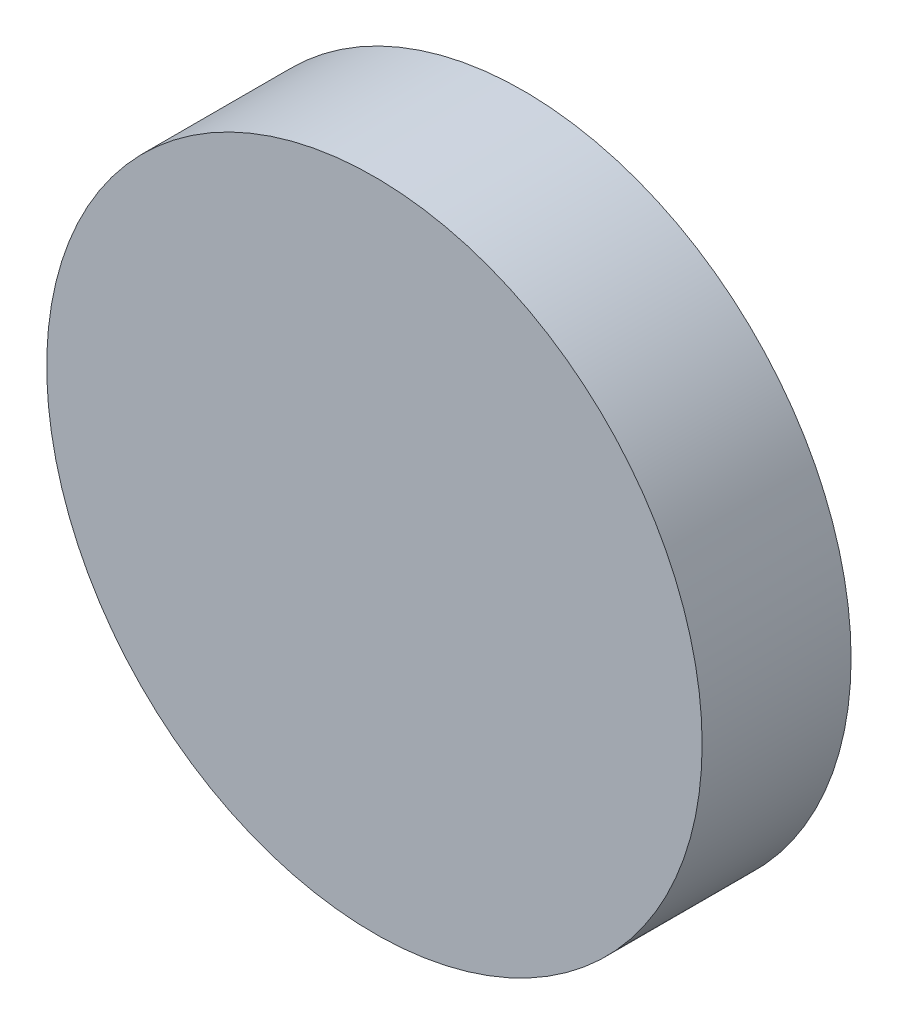
SolidWorks part; units mm, degrees
ref_plane "前视基准面" through (0, 0, 0) normal (0, 0, 1) x (1, 0, 0)
ref_plane "上视基准面" through (0, 0, 0) normal (0, 1, 0) x (1, 0, 0)
ref_plane "右视基准面" through (0, 0, 0) normal (1, 0, 0) x (0, 0, -1)
other "Configuration Table"
sketch "草图1" plane through (0, 0, 0) normal (0, 0, 1) x (1, 0, 0)
  circle A0 centre (0, 0) radius 55
extrude "凸台-拉伸1" add sketch "草图1" against normal blind 25
sketch "草图2" plane through (0, 0, 0) normal (0, 0, 1) x (1, 0, 0)
  circle A0 centre (0, 0) radius 12
sketch "草图3" plane through (0, 0, 0) normal (0, 0, 1) x (1, 0, 0)
  circle A0 centre (35, 0) radius 8
